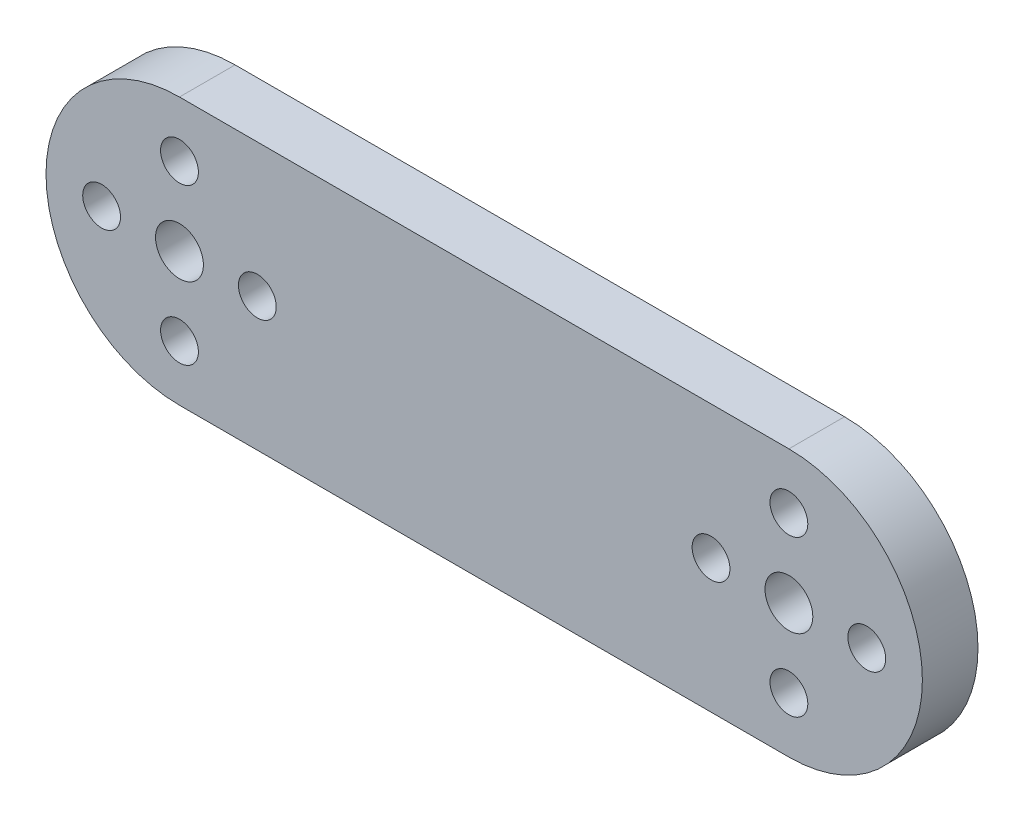
SolidWorks part; units mm, degrees
ref_plane "Płaszczyzna przednia" through (0, 0, 0) normal (0, 0, 1) x (1, 0, 0)
ref_plane "Płaszczyzna górna" through (0, 0, 0) normal (0, 1, 0) x (1, 0, 0)
ref_plane "Płaszczyzna prawa" through (0, 0, 0) normal (1, 0, 0) x (0, 0, -1)
sketch "Szkic1" plane through (0, 0, 0) normal (0, 0, 1) x (1, 0, 0)
  line L0 (0, 0) -> (-54.7848, 0) construction
  line L1 (0, -12) -> (-54.7848, -12)
  line L2 (0, 12) -> (-54.7848, 12)
  line L3 (-27.3924, 12) -> (-27.3924, -18.4536) construction
  circle A0 centre (0, 7.001) radius 1.7
  circle A1 centre (0, 0) radius 7.001 construction
  circle A5 centre (0, 0) radius 2.15
  circle A6 centre (7.001, 0) radius 1.7
  circle A7 centre (0, -7.001) radius 1.7
  circle A8 centre (-7.001, 0) radius 1.7
  arc A9 (0, -12) -> (0, 12) centre (0, 0) ccw
  arc A10 (-54.7848, 12) -> (-54.7848, -12) centre (-54.7848, 0) ccw
  circle A11 centre (-54.7848, 0) radius 7.001 construction
  circle A12 centre (-47.7837, 0) radius 1.7
  circle A13 centre (-54.7848, -7.001) radius 1.7
  circle A14 centre (-61.7858, 0) radius 1.7
  circle A15 centre (-54.7848, 0) radius 2.15
  circle A16 centre (-54.7848, 7.001) radius 1.7
  point P3 (-27.3924, 0)
  point P9 (0, 0)
  point P17 (0, 0)
  point P34 (-54.7848, 0)
  point P35 (-54.7848, 0)
  dimension "D1" = 3.4
  dimension "D2" = 4.3
  dimension "D3" = 14.0021
  dimension "D5" = 12
  dimension "D4" = 4
extrude "Dodanie-wyciągnięcie1" add sketch "Szkic1" along normal blind 5
